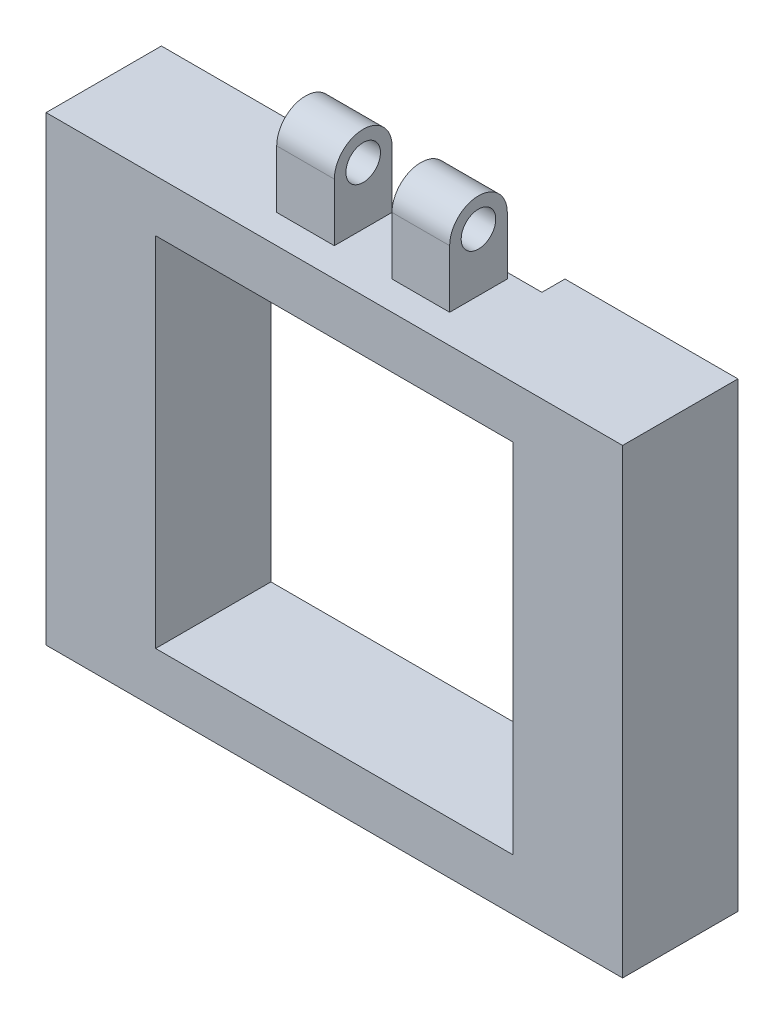
SolidWorks part; units mm, degrees
ref_plane "Front Plane" through (0, 0, 0) normal (0, 0, 1) x (1, 0, 0)
ref_plane "Top Plane" through (0, 0, 0) normal (0, 1, 0) x (1, 0, 0)
ref_plane "Right Plane" through (0, 0, 0) normal (1, 0, 0) x (0, 0, -1)
sketch "Sketch1" plane through (669.8418, 0, 0) normal (0, 0, 1) x (1, 0, 0)
  line L1 (-696.3103, 457.6379) -> (-646.3103, 457.6379)
  line L2 (-696.3103, 457.6379) -> (-696.3103, 417.6379)
  line L3 (-696.3103, 417.6379) -> (-646.3103, 417.6379)
  line L4 (-646.3103, 457.6379) -> (-646.3103, 417.6379)
  dimension "50" = 50
  dimension "D2" = 40
extrude "Boss-Extrude1" add sketch "Sketch1" along normal blind 10
sketch "Sketch5" plane through (23.5315, 0, 0) normal (1, 0, 0) x (0, 0, -1)
  line L0 (0, 417.6379) -> (0, 457.6379) construction
  line L1 (-8, 445.1379) -> (-2, 445.1379)
  line L2 (-8, 445.1379) -> (-8, 440.1379)
  line L3 (-8, 440.1379) -> (-2, 440.1379)
  line L4 (-2, 445.1379) -> (-2, 440.1379)
  line L5 (-8, 435.1379) -> (-2, 435.1379)
  line L6 (-8, 435.1379) -> (-8, 430.1379)
  line L7 (-8, 430.1379) -> (-2, 430.1379)
  line L8 (-2, 435.1379) -> (-2, 430.1379)
  line L9 (-10, 417.6379) -> (-10, 457.6379) construction
  line L10 (0, 437.6379) -> (-10, 437.6379)
  line L11 (-2, 440.1379) -> (-2, 437.6379)
  line L12 (-8, 435.1379) -> (-8, 437.6379)
  dimension "D1" = 5
  dimension "D2" = 2
  dimension "D3" = 2
  dimension "D4" = 2
  dimension "D5" = 2
  dimension "D6" = 5
  dimension "D7" = 5
extrude "Boss-Extrude3" add sketch "Sketch5" along normal blind 10 contours L4 L1 L2 L3 | L8 L5 L6 L7
sketch "Sketch6" plane through (669.8418, 445.1379, 0) normal (0, 1, 0) x (1, 0, 0)
  line L1 (-646.3103, -8) -> (-646.3103, -2) construction
  line L2 (-646.3103, -5) -> (-636.3103, -5) construction
  line L3 (-636.3103, -8) -> (-636.3103, -2) construction
  line L4 (-641.3103, -8) -> (-641.3103, -2) construction
  line L5 (-636.3103, -8) -> (-646.3103, -8) construction
  line L6 (-636.3103, -2) -> (-646.3103, -2) construction
  circle A1 centre (-641.3103, -5) radius 2
extrude "Cut-Extrude1" cut sketch "Sketch6" against normal blind 20
sketch "Sketch8" plane through (-26.4685, 0, 0) normal (-1, 0, 0) x (0, 0, 1)
  line L1 (0, 417.6379) -> (10, 417.6379)
  line L2 (0, 417.6379) -> (0, 457.6379)
  line L3 (0, 457.6379) -> (10, 457.6379)
  line L4 (10, 417.6379) -> (10, 457.6379)
extrude "Cut-Extrude2" cut sketch "Sketch8" against normal blind 25
sketch "Sketch9" plane through (0, 435.1379, 0) normal (0, 1, 0) x (1, 0, 0)
  line L1 (23.5315, -8) -> (33.5315, -8)
  line L2 (23.5315, -8) -> (23.5315, -2)
  line L3 (23.5315, -2) -> (33.5315, -2)
  line L4 (33.5315, -8) -> (33.5315, -2)
  circle A0 centre (28.5315, -5) radius 1.9309
extrude "Boss-Extrude4" add sketch "Sketch9" along normal blind 5
sketch "Sketch10" plane through (0, 0, 8) normal (0, 0, 1) x (1, 0, 0)
  line L0 (23.5315, 417.6379) -> (23.5315, 457.6379) construction
  line L1 (33.5315, 430.1379) -> (23.5315, 430.1379)
  line L2 (33.5315, 430.1379) -> (33.5315, 435.1379)
  line L3 (33.5315, 435.1379) -> (23.5315, 435.1379)
  line L4 (23.5315, 430.1379) -> (23.5315, 435.1379)
  line L6 (33.5315, 445.1379) -> (23.5315, 445.1379)
  line L7 (33.5315, 445.1379) -> (33.5315, 440.1379)
  line L8 (33.5315, 440.1379) -> (23.5315, 440.1379)
  line L9 (23.5315, 445.1379) -> (23.5315, 440.1379)
  dimension "D1" = 5
  dimension "D2" = 5
extrude "Cut-Extrude3" cut sketch "Sketch10" against normal blind 15 contours L7 L6 L9 L8 | L2 L1 L4 L3
mirror "Mirror1" about plane through (-1.4685, 0, 0) normal (1, 0, 0) of "Boss-Extrude1"
sketch "Sketch11" plane through (0, 457.6379, 0) normal (0, 1, 0) x (1, 0, 0)
  line L0 (23.5315, 0) -> (-26.4685, 0) construction
  line L1 (-3.9685, -2.5) -> (1.0315, -2.5)
  line L2 (-3.9685, -2.5) -> (-3.9685, -7.5)
  line L3 (-3.9685, -7.5) -> (1.0315, -7.5)
  line L4 (1.0315, -2.5) -> (1.0315, -7.5)
  line L5 (23.5315, -10) -> (-26.4685, -10) construction
  line L6 (23.5315, -10) -> (23.5315, 0) construction
  line L7 (-26.4685, -10) -> (-26.4685, 0) construction
  dimension "D1" = 2.5
  dimension "D2" = 2.5
  dimension "D3" = 22.5
  dimension "D4" = 22.5
extrude "Boss-Extrude5" add sketch "Sketch11" along normal blind 10
sketch "Sketch12" plane through (1.0315, 0, 0) normal (1, 0, 0) x (0, 0, -1)
  line L0 (-5, 467.6379) -> (-5, 457.6379) construction
  line L1 (-7.5, 467.6379) -> (-2.5, 467.6379) construction
  line L2 (-7.5, 457.6379) -> (-2.5, 457.6379) construction
  line L3 (-2.5, 462.6379) -> (-7.5, 462.6379) construction
  line L4 (-2.5, 467.6379) -> (-2.5, 457.6379) construction
  line L5 (-7.5, 467.6379) -> (-7.5, 457.6379) construction
  circle A1 centre (-5, 462.6379) radius 1.5
  dimension "D1" = 3
extrude "Cut-Extrude4" cut sketch "Sketch12" against normal blind 10
sketch "Sketch13" plane through (33.5315, 0, 0) normal (1, 0, 0) x (0, 0, -1)
  line L1 (-8, 435.1379) -> (-2, 435.1379)
  line L2 (-8, 435.1379) -> (-8, 440.1379)
  line L3 (-8, 440.1379) -> (-2, 440.1379)
  line L4 (-2, 435.1379) -> (-2, 440.1379)
extrude "Cut-Extrude5" cut sketch "Sketch13" against normal blind 10
sketch "Sketch15" plane through (0, 457.6379, 0) normal (0, 1, 0) x (1, 0, 0)
  line L1 (-8.9685, -7.5) -> (-3.9685, -7.5)
  line L2 (-8.9685, -7.5) -> (-8.9685, -2.5)
  line L3 (-8.9685, -2.5) -> (-3.9685, -2.5)
  line L4 (-3.9685, -7.5) -> (-3.9685, -2.5)
  line L5 (6.0315, -7.5) -> (1.0315, -7.5)
  line L6 (6.0315, -7.5) -> (6.0315, -2.5)
  line L7 (6.0315, -2.5) -> (1.0315, -2.5)
  line L8 (1.0315, -7.5) -> (1.0315, -2.5)
  dimension "D1" = 5
  dimension "D2" = 5
  dimension "D3" = 5
  dimension "D4" = 5
sketch "Sketch18" plane through (0, 467.6379, 0) normal (0, 1, 0) x (1, 0, 0)
  line L1 (-3.9685, -2.5) -> (1.0315, -2.5)
  line L2 (-3.9685, -2.5) -> (-3.9685, -7.5)
  line L3 (-3.9685, -7.5) -> (1.0315, -7.5)
  line L4 (1.0315, -2.5) -> (1.0315, -7.5)
extrude "Boss-Extrude7" add sketch "Sketch15" along normal blind 10
extrude "Cut-Extrude7" cut sketch "Sketch18" against normal blind 10
sketch "Sketch19" plane through (-8.9685, 0, 0) normal (-1, 0, 0) x (0, 0, 1)
  line L0 (5, 467.6379) -> (5, 457.6379) construction
  line L1 (7.5, 467.6379) -> (2.5, 467.6379) construction
  line L2 (10, 457.6379) -> (0, 457.6379) construction
  line L3 (7.5, 462.6379) -> (2.5, 462.6379) construction
  line L4 (7.5, 467.6379) -> (7.5, 457.6379) construction
  line L5 (2.5, 467.6379) -> (2.5, 457.6379) construction
  circle A0 centre (5, 462.6379) radius 1.5
extrude "Cut-Extrude8" cut sketch "Sketch19" against normal blind 43
sketch "Sketch20" plane through (6.0315, 0, 0) normal (1, 0, 0) x (0, 0, -1)
  line L0 (-7.5, 462.6379) -> (-7.5, 467.6379)
  line L1 (-7.5, 467.6379) -> (-2.5, 467.6379)
  line L2 (-2.5, 467.6379) -> (-2.5, 462.6379)
  circle A0 centre (-5, 462.6379) radius 2.5
  line M3 (-2.5, 457.6379) -> (-2.5, 467.6379)
  line M4 (-2.5, 467.6379) -> (-7.5, 467.6379)
  line M5 (-7.5, 467.6379) -> (-7.5, 457.6379)
extrude "Cut-Extrude9" cut sketch "Sketch20" against normal blind 20 contours A0 M3 M4 M5
sketch "Sketch21" plane through (0, 0, 10) normal (0, 0, 1) x (1, 0, 0)
  line L0 (23.5315, 457.6379) -> (-26.4685, 457.6379) construction
  line L1 (-16.9685, 453.1379) -> (14.0315, 453.1379)
  line L2 (-16.9685, 453.1379) -> (-16.9685, 422.1379)
  line L3 (-16.9685, 422.1379) -> (14.0315, 422.1379)
  line L4 (14.0315, 453.1379) -> (14.0315, 422.1379)
  line L5 (23.5315, 417.6379) -> (23.5315, 457.6379) construction
  point P4 (-1.4685, 457.6379)
  point P7 (-1.4685, 453.1379)
  point P10 (23.5315, 437.6379)
  point P11 (14.0315, 437.6379)
  dimension "D1" = 31
  dimension "D2" = 31
extrude "Cut-Extrude10" cut sketch "Sketch21" against normal blind 30
sketch "Sketch22" plane through (0, 0, 0) normal (0, 0, -1) x (-1, 0, 0)
  line L0 (-8.5315, 452.6387) -> (-8.5315, 457.6379)
  line L1 (-8.5315, 452.6387) -> (11.4685, 452.6387)
  line L2 (-8.5315, 457.6379) -> (11.4685, 457.6379)
  line L3 (11.4685, 452.6387) -> (11.4685, 457.6379)
  line L4 (-8.5315, 452.6387) -> (11.4685, 457.6379) construction
  line L5 (-8.5315, 457.6379) -> (11.4685, 452.6387) construction
  line L6 (-23.5315, 457.6379) -> (26.4685, 457.6379) construction
  point P0 (0, 0)
  point P1 (1.4685, 455.1383)
  point P8 (1.4685, 457.6379)
  dimension "D1" = 20
extrude "Cut-Extrude11" cut sketch "Sketch22" against normal blind 2
